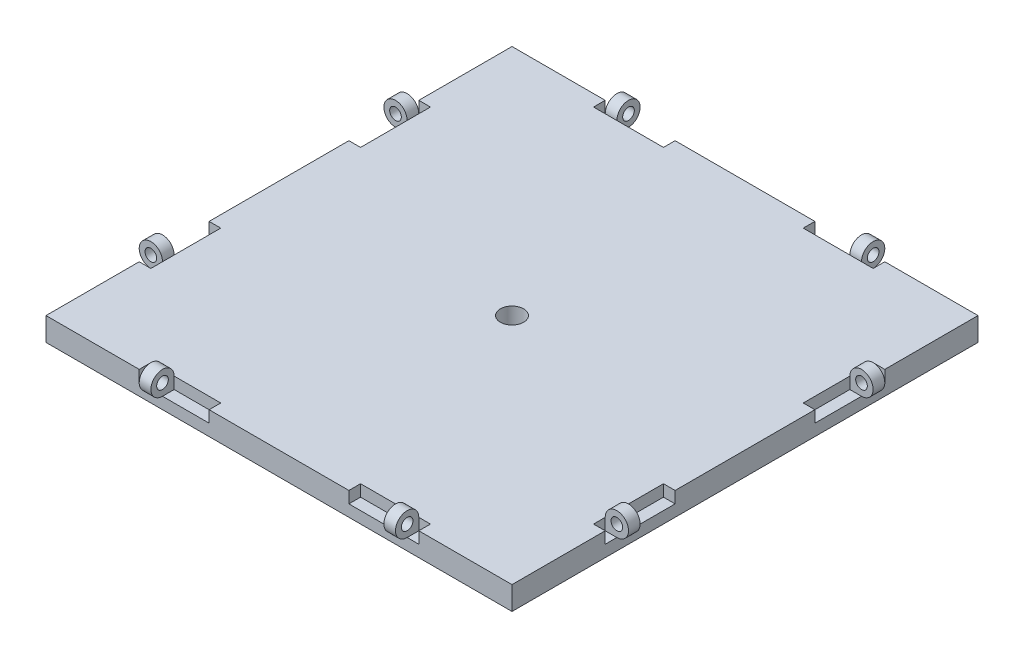
SolidWorks part; units mm, degrees
material "PET"
ref_plane "Front Plane" through (0, 0, 0) normal (0, 0, 1) x (1, 0, 0)
ref_plane "Top Plane" through (0, 0, 0) normal (0, 1, 0) x (1, 0, 0)
ref_plane "Right Plane" through (0, 0, 0) normal (1, 0, 0) x (0, 0, -1)
sketch "Sketch1" plane through (0, 0, 0) normal (0, 1, 0) x (1, 0, 0)
  line L0 (-100, 100) -> (100, 100)
  line L1 (-100, 100) -> (-100, -100)
  line L2 (100, 100) -> (100, -100)
  line L3 (-100, -100) -> (100, -100)
  circle A0 centre (0, 0) radius 5
  dimension "D5" = 10
  dimension "D1" = 200
  dimension "D2" = 200
  dimension "D3" = 100
  dimension "D4" = 100
extrude "Boss-Extrude1" add sketch "Sketch1" along normal blind 10 contours L1 L3 L2 L0 A0
sketch "Sketch2" plane through (0, 10, 0) normal (0, 1, 0) x (1, 0, 0)
  line L0 (30, 100) -> (60, 100)
  line L1 (30, 100) -> (30, 95)
  line L2 (60, 100) -> (60, 95)
  line L3 (30, 95) -> (60, 95)
  line L5 (0, 0) -> (0, 10.1919) construction
  line L6 (-30, 95) -> (-60, 95)
  line L7 (-60, 100) -> (-60, 95)
  line L8 (-30, 100) -> (-30, 95)
  line L9 (-30, 100) -> (-60, 100)
  line L10 (-100, 100) -> (100, 100) construction
  dimension "D1" = 5
  dimension "D2" = 30
  dimension "D3" = 120
extrude "Cut-Extrude1" cut sketch "Sketch2" against normal blind 5
sketch "Sketch3" plane through (60, 0, 0) normal (-1, 0, 0) x (0, 0, 1)
  circle A0 centre (-100, 10) radius 5
  circle A1 centre (-100, 10) radius 2.5
  line M1 (-95, 10) -> (-100, 10)
  line M2 (-100, 10) -> (-100, 5)
  line M3 (-100, 5) -> (-95, 5)
  line M4 (-95, 5) -> (-95, 10)
  dimension "D1" = 5
extrude "Boss-Extrude3" add sketch "Sketch3" along normal blind 5 from offset 5 contours A1 A0 M1 M2 | A1 A0 M2 M1 | A0 M3 M4
mirror "Mirror1" about plane through (0, 0, 0) normal (1, 0, 0) of "Boss-Extrude3"
pattern_circular "CirPattern1" count 4 over 360 about axis through (0, 0, 0) along (0, 1, 0) of "Cut-Extrude1", "Boss-Extrude3", "Mirror1"
